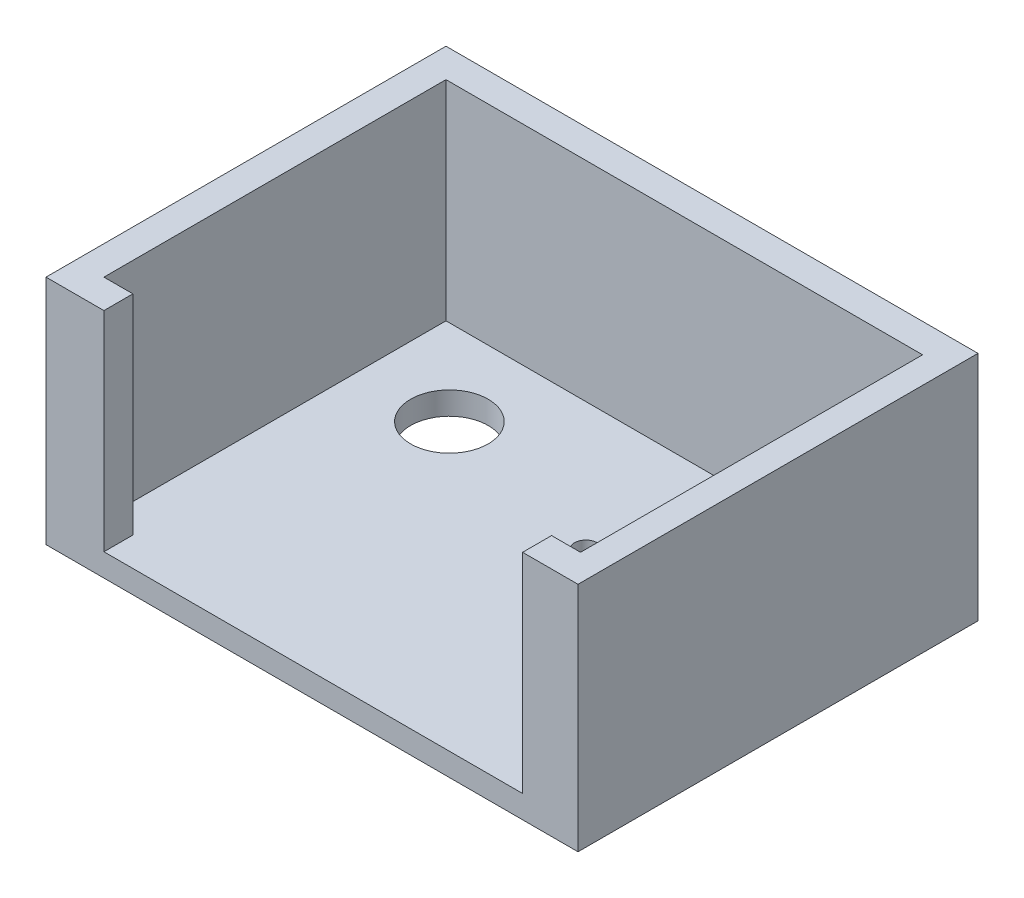
SolidWorks part; units mm, degrees
ref_plane "Front Plane" through (0, 0, 0) normal (0, 0, 1) x (1, 0, 0)
ref_plane "Top Plane" through (0, 0, 0) normal (0, 1, 0) x (1, 0, 0)
ref_plane "Right Plane" through (0, 0, 0) normal (1, 0, 0) x (0, 0, -1)
sketch "Sketch1" plane through (0, 0, 0) normal (0, 1, 0) x (1, 0, 0)
  line L1 (0, 0) -> (23.33, 0)
  line L2 (0, 0) -> (0, 17.54)
  line L3 (0, 17.54) -> (23.33, 17.54)
  line L4 (23.33, 0) -> (23.33, 17.54)
  dimension "D1" = 23.33
  dimension "D2" = 17.54
extrude "Boss-Extrude1" add sketch "Sketch1" along normal blind 10.16
sketch "Sketch2" plane through (0, 10.16, 0) normal (0, 1, 0) x (1, 0, 0)
  line L0 (0, 17.54) -> (0, 0) construction
  line L1 (1.27, 1.27) -> (22.17, 1.27)
  line L2 (1.27, 1.27) -> (1.27, 16.27)
  line L3 (1.27, 16.27) -> (22.17, 16.27)
  line L4 (22.17, 1.27) -> (22.17, 16.27)
  line L5 (0, 0) -> (23.33, 0) construction
  dimension "D1" = 1.27
  dimension "D2" = 1.27
  dimension "D3" = 20.9
  dimension "D4" = 15
extrude "Cut-Extrude1" cut sketch "Sketch2" against normal blind 9.16
sketch "Sketch3" plane through (0, 1, 0) normal (0, 1, 0) x (1, 0, 0)
  line L0 (22.17, 16.27) -> (1.27, 16.27) construction
  line L1 (11.72, 16.27) -> (11.72, 3.1132)
  circle A0 centre (5.17, 12.52) radius 1.7
  circle A1 centre (18.27, 12.52) radius 1.7
  circle A2 centre (13.015, 10.66) radius 0.5
  dimension "D1" = 3.4
  dimension "D2" = 3.4
  dimension "D5" = 6.55
  dimension "D6" = 6.55
  dimension "D7" = 5.255
  dimension "D8" = 1.86
  dimension "D9" = 1
  dimension "D3" = 3.75
  dimension "D4" = 3.75
extrude "Cut-Extrude2" cut sketch "Sketch3" against normal through all contours A0 | A1 | A2
sketch "Sketch4" plane through (0, 0, -1.27) normal (0, 0, -1) x (-1, 0, 0)
  line L0 (-1.27, 1) -> (-22.17, 1) construction
  line L1 (-20.9, 1) -> (-2.54, 1)
  line L2 (-20.9, 1) -> (-20.9, 13.0119)
  line L3 (-20.9, 13.0119) -> (-2.54, 13.0119)
  line L4 (-2.54, 1) -> (-2.54, 13.0119)
  line L5 (-22.17, 1) -> (-22.17, 10.16) construction
  line L6 (-1.27, 1) -> (-1.27, 10.16) construction
  dimension "D1" = 12.0119
  dimension "D2" = 1.27
  dimension "D3" = 1.27
extrude "Cut-Extrude3" cut sketch "Sketch4" against normal through all
